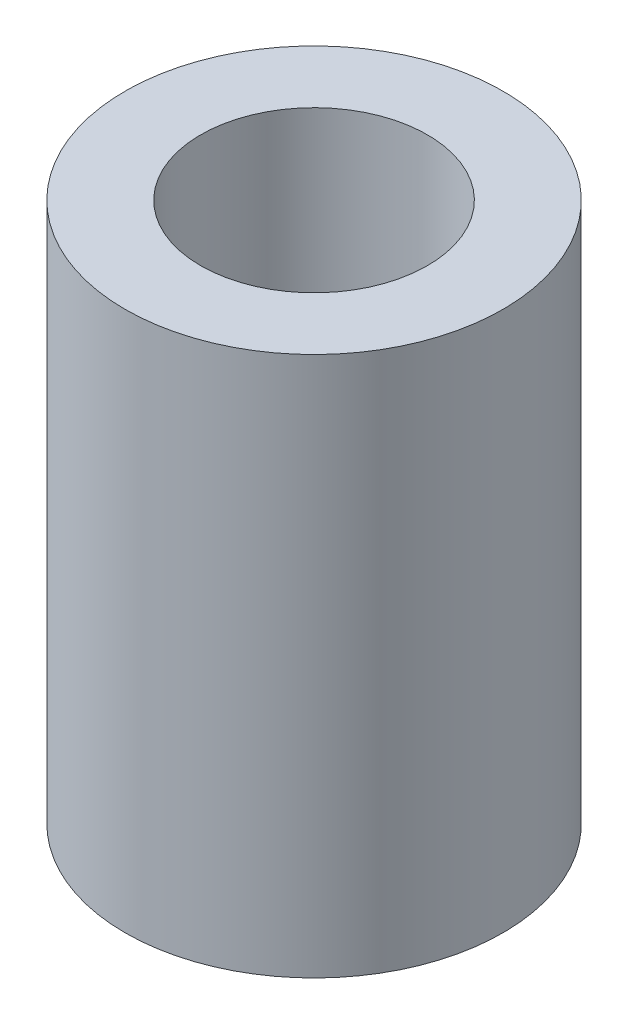
SolidWorks part; units mm, degrees
material "ABS"
ref_plane "前视基准面" through (0, 0, 0) normal (0, 0, 1) x (1, 0, 0)
ref_plane "上视基准面" through (0, 0, 0) normal (0, 1, 0) x (1, 0, 0)
ref_plane "右视基准面" through (0, 0, 0) normal (1, 0, 0) x (0, 0, -1)
sketch "草图1" plane through (0, 0, 0) normal (0, 1, 0) x (1, 0, 0)
  circle A0 centre (0, 0) radius 2.1
  circle A1 centre (0, 0) radius 3.5
  dimension "D1" = 7
  dimension "D2" = 4.2
extrude "凸台-拉伸1" add sketch "草图1" along normal blind 10
